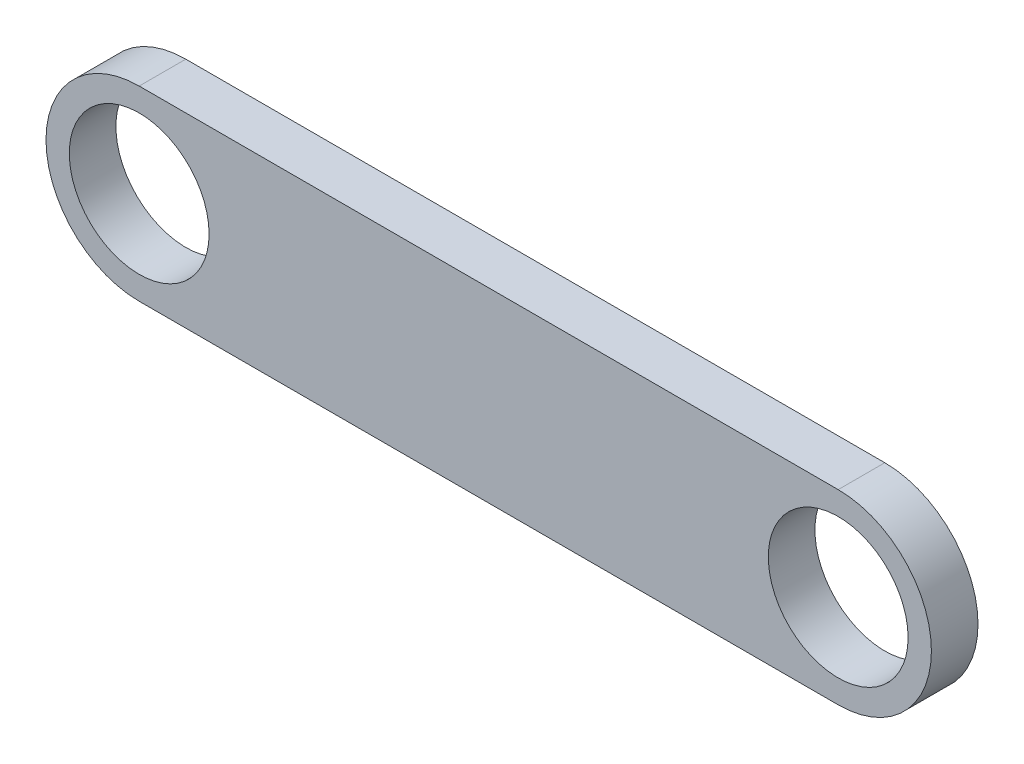
SolidWorks part; units mm, degrees
ref_plane "Спереди" through (0, 0, 0) normal (0, 0, 1) x (1, 0, 0)
ref_plane "Сверху" through (0, 0, 0) normal (0, 1, 0) x (1, 0, 0)
ref_plane "Справа" through (0, 0, 0) normal (1, 0, 0) x (0, 0, -1)
other "Configuration Table"
sketch "Эскиз1" plane through (0, 0, 0) normal (0, 0, 1) x (1, 0, 0)
  line L0 (0, 0) -> (150, 0) construction
  line L1 (0, 20) -> (150, 20)
  line L2 (0, -20) -> (150, -20)
  arc A0 (0, 20) -> (0, -20) centre (0, 0) ccw
  arc A1 (150, -20) -> (150, 20) centre (150, 0) ccw
  circle A2 centre (0, 0) radius 15
  circle A3 centre (150, 0) radius 15
  point P3 (75, 0)
  dimension "D3" = 30
  dimension "D4" = 30
  dimension "D1" = 150
  dimension "D2" = 40
extrude "Бобышка-Вытянуть1" add sketch "Эскиз1" along normal blind 10
